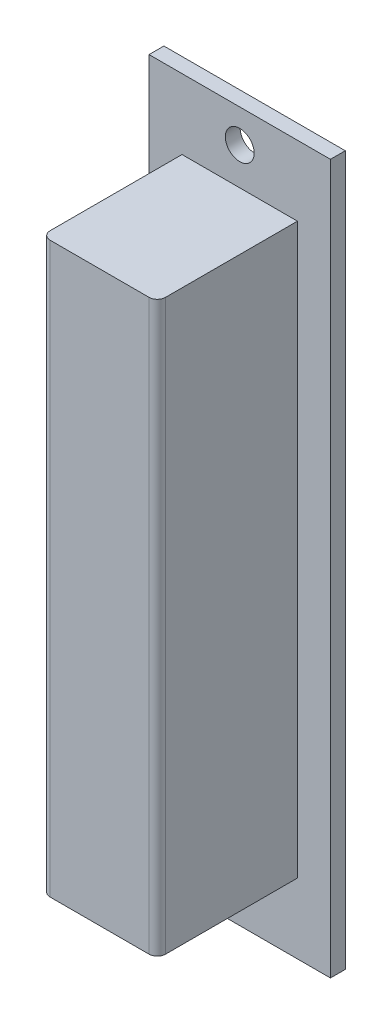
SolidWorks part; units mm, degrees
ref_plane "前视基准面" through (0, 0, 0) normal (0, 0, 1) x (1, 0, 0)
ref_plane "上视基准面" through (0, 0, 0) normal (0, 1, 0) x (1, 0, 0)
ref_plane "右视基准面" through (0, 0, 0) normal (1, 0, 0) x (0, 0, -1)
sketch "草图1" plane through (0, 0, 0) normal (0, 0, 1) x (1, 0, 0)
  line L0 (0, 48.626) -> (0, -83.7004) construction
  line L1 (-92.2698, 0) -> (95.8569, 0) construction
  line L2 (-11, 43) -> (11, 43)
  line L3 (-11, 43) -> (-11, -43)
  line L4 (-11, -43) -> (11, -43)
  line L5 (11, -43) -> (11, 43)
  circle A0 centre (0, 39) radius 1.75
  circle A1 centre (0, -39) radius 1.75
  dimension "D3" = 78
  dimension "D4" = 3.5
  dimension "D1" = 22
  dimension "D2" = 86
extrude "拉伸1" add sketch "草图1" along normal blind 1.8
sketch "草图2" plane through (0, 0, 1.8) normal (0, 0, 1) x (1, 0, 0)
  line L0 (0, 37.5456) -> (0, -35.199) construction
  line L1 (-34.3867, 0) -> (34.7477, 0) construction
  line L2 (-7, 34.5) -> (7, 34.5)
  line L3 (-7, 34.5) -> (-7, -34.5)
  line L4 (-7, -34.5) -> (7, -34.5)
  line L5 (7, -34.5) -> (7, 34.5)
  dimension "D1" = 14
  dimension "D2" = 69
extrude "拉伸2" add sketch "草图2" along normal blind 17
fillet "圆角1" radius 1 2 edges at (-7, 0, 18.8) (7, 0, 18.8)
